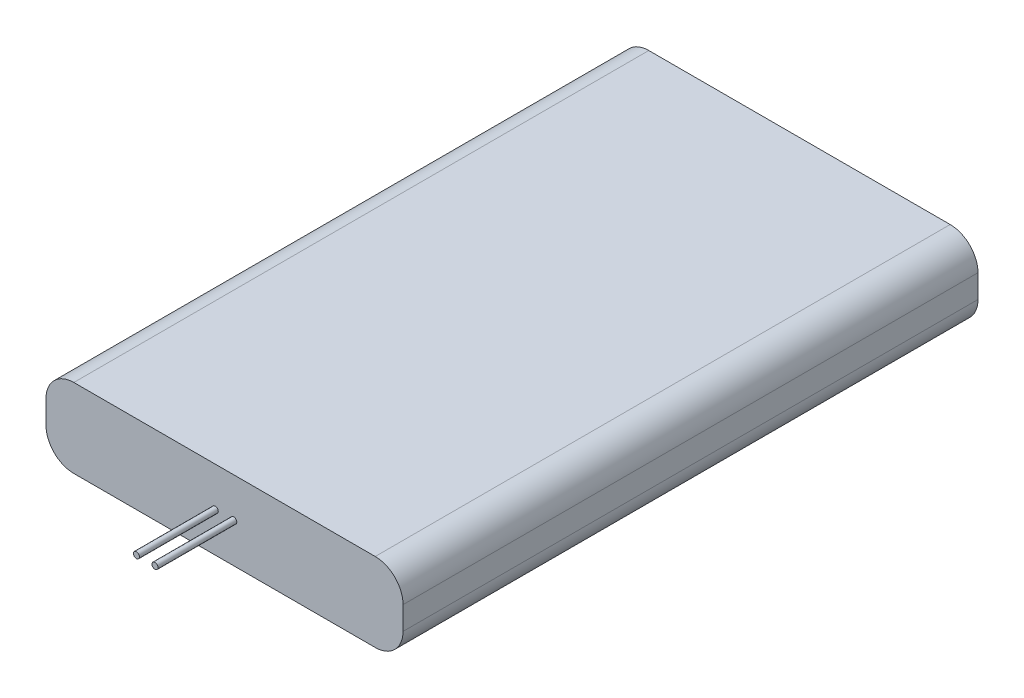
SolidWorks part; units mm, degrees
ref_plane "Front Plane" through (0, 0, 0) normal (0, 0, 1) x (1, 0, 0)
ref_plane "Top Plane" through (0, 0, 0) normal (0, 1, 0) x (1, 0, 0)
ref_plane "Right Plane" through (0, 0, 0) normal (1, 0, 0) x (0, 0, -1)
sketch "Sketch1" plane through (0, 0, 0) normal (0, 1, 0) x (1, 0, 0)
  line L1 (-19.25, -31) -> (19.25, -31)
  line L2 (-19.25, -31) -> (-19.25, 31)
  line L3 (-19.25, 31) -> (19.25, 31)
  line L4 (19.25, -31) -> (19.25, 31)
  line L5 (-19.25, -31) -> (19.25, 31) construction
  line L6 (-19.25, 31) -> (19.25, -31) construction
  point P0 (0, 0)
  dimension "D1" = 38.5
  dimension "D2" = 62
extrude "Boss-Extrude1" add sketch "Sketch1" along normal blind 8.5
fillet "Fillet1" radius 3 4 edges at (-19.25, 0, 0) (-19.25, 8.5, 0) (19.25, 0, 0) (19.25, 8.5, 0)
sketch "Sketch2" plane through (0, 0, 31) normal (0, 0, 1) x (1, 0, 0)
  line L0 (0, 8.5) -> (0, 0) construction
  line L1 (-16.25, 8.5) -> (16.25, 8.5) construction
  line L2 (-19.25, 4.25) -> (19.25, 4.25) construction
  line L3 (-19.25, 5.5) -> (-19.25, 3) construction
  line L4 (19.25, 5.5) -> (19.25, 3) construction
  circle A0 centre (-1, 4.25) radius 0.325
  circle A1 centre (1, 4.25) radius 0.325
  point P15 (0, 0)
  dimension "D1" = 0.65
  dimension "D2" = 1
extrude "Boss-Extrude2" add sketch "Sketch2" along normal blind 8.5
